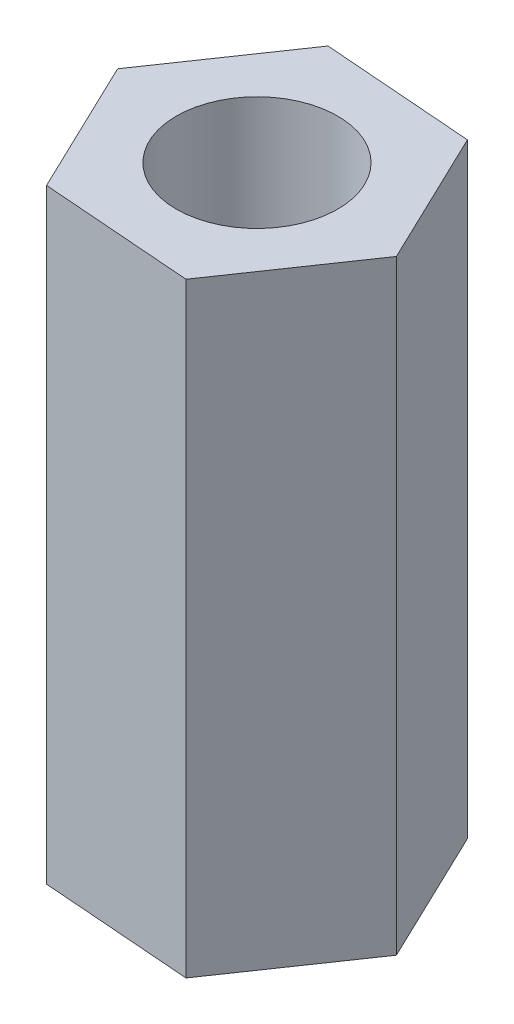
SolidWorks part; units mm, degrees
ref_plane "前视基准面" through (0, 0, 0) normal (0, 0, 1) x (1, 0, 0)
ref_plane "上视基准面" through (0, 0, 0) normal (0, 1, 0) x (1, 0, 0)
ref_plane "右视基准面" through (0, 0, 0) normal (1, 0, 0) x (0, 0, -1)
other "Configuration Table"
sketch "草图1" plane through (0, 0, 0) normal (0, 1, 0) x (1, 0, 0)
  line L1 (1.2984, -2.7069) -> (2.9935, -0.229)
  line L2 (2.9935, -0.229) -> (1.695, 2.4779)
  line L3 (1.695, 2.4779) -> (-1.2984, 2.7069)
  line L4 (-1.2984, 2.7069) -> (-2.9935, 0.229)
  line L5 (-2.9935, 0.229) -> (-1.695, -2.4779)
  line L6 (-1.695, -2.4779) -> (1.2984, -2.7069)
  circle A0 centre (0, 0) radius 2.6 construction
  circle A1 centre (0, 0) radius 1.6
  dimension "D1" = 5.2
  dimension "D2" = 3.2
extrude "凸台-拉伸1" add sketch "草图1" along normal blind 12
